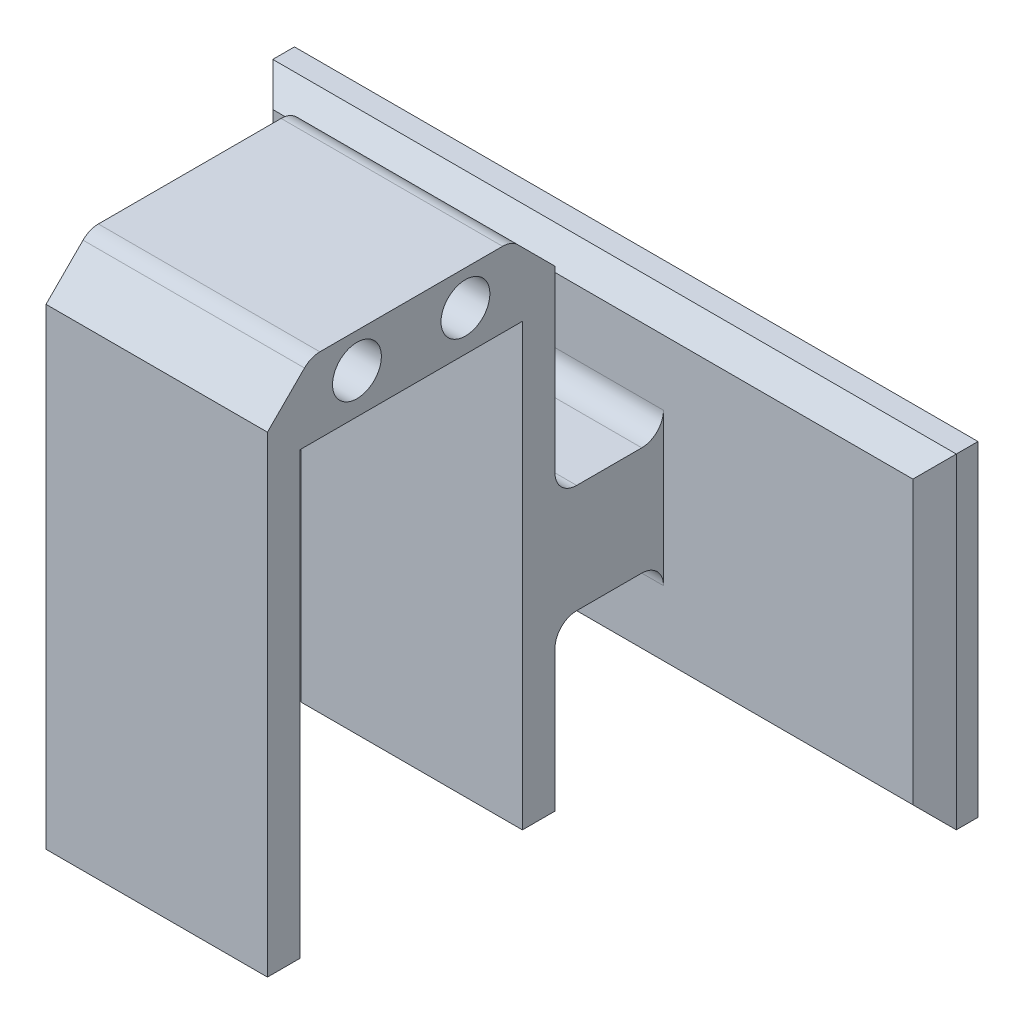
SolidWorks part; units mm, degrees
ref_plane "Front Plane" through (0, 0, 0) normal (0, 0, 1) x (1, 0, 0)
ref_plane "Top Plane" through (0, 0, 0) normal (0, 1, 0) x (1, 0, 0)
ref_plane "Right Plane" through (0, 0, 0) normal (1, 0, 0) x (0, 0, -1)
sketch "Sketch1" plane through (0, 0, 0) normal (1, 0, 0) x (0, 0, -1)
  line L0 (-10.25, 20.3) -> (10.25, 20.3)
  line L1 (-10.25, -20.3) -> (10.25, -20.3)
  line L2 (-10.25, -20.3) -> (-10.25, 20.3)
  line L4 (10.25, -20.3) -> (10.25, 20.3)
  line L5 (-10.25, -20.3) -> (-13.25, -20.3)
  line L6 (-13.25, -20.3) -> (-13.25, 29.7)
  line L7 (-13.25, 29.7) -> (13.25, 29.7)
  line L8 (10.25, -20.3) -> (13.25, -20.3)
  line L11 (-10.05, 20.1) -> (10.05, 20.1)
  line L13 (13.25, -20.3) -> (13.25, 29.7)
  point P5 (0, 20.3)
  point P6 (-10.25, 0)
  line B0 (-8.8772, 20.1) -> (-10.8742, 20.1) construction
  line B1 (7.4, 20.1) -> (11.2713, 20.1) construction
  line B2 (10.05, 18.0597) -> (10.05, 22.3295) construction
  line B3 (-3.2, -20.1) -> (-12.1258, -20.1) construction
  line B4 (-10.05, -15.1145) -> (-10.05, -21.3251) construction
  line B5 (-10.05, -20.1) -> (10.05, -20.1)
  line B6 (-10.05, -20.1) -> (-10.05, 20.1)
  line B7 (10.05, -20.1) -> (10.05, 20.1)
  circle B8 centre (-5, 24) radius 2.25
  circle B9 centre (5, 24) radius 2.25
  dimension "D1" = 0.2
  dimension "D2" = 0.2
  dimension "D3" = 0.2
  dimension "D4" = 0.2
  dimension "D5" = 3
  dimension "D6" = 50
  dimension "D7" = 3
sketch_block_instance "Block1-1"
sketch_block "Block1"
extrude "Boss-Extrude1" add sketch "Sketch1" along normal blind 20 contours L8 L13 L7 L6 L5 L2 L0 L4 B9 B8
sketch "Sketch2" plane through (0, 0, 0) normal (-1, 0, 0) x (0, 0, 1)
  circle A0 centre (-5, 24) radius 2.25
  circle A1 centre (5, 24) radius 2.25
extrude "Boss-Extrude2" add sketch "Sketch2" against normal blind 10
sketch "Sketch4" plane through (20, 0, 0) normal (1, 0, 0) x (0, 0, -1)
  line L0 (13.25, -20.3) -> (13.25, 29.7) construction
  line L1 (-13.25, 29.7) -> (13.25, 29.7)
  line L2 (-13.25, 29.7) -> (-13.25, 27.2)
  line L3 (-13.25, 27.2) -> (13.25, 27.2)
  line L4 (13.25, 29.7) -> (13.25, 27.2)
  dimension "D1" = 2.5
extrude "Cut-Extrude1" cut sketch "Sketch4" against normal through all
chamfer "Chamfer2" distance 4 angle 45 1 edges at (10, 27.2, -13.25)
chamfer "Chamfer3" distance 4 angle 45 1 edges at (10, 27.2, 13.25)
fillet "Fillet4" radius 2 2 edges at (10, 27.2, -9.25) (10, 27.2, 9.25)
sketch "Sketch7" plane through (20, 0, 0) normal (1, 0, 0) x (0, 0, -1)
  line L0 (13.25, -20.3) -> (13.25, 23.2) construction
  line L3 (23.25, -5.3) -> (13.25, -5.3)
  line L5 (10.25, -20.3) -> (13.25, -20.3) construction
  line L6 (13.25, 4.7) -> (23.25, 4.7)
  line L8 (23.25, 4.7) -> (23.25, -5.3)
  line L9 (13.25, 4.7) -> (13.25, -5.3)
  dimension "D1" = 10
  dimension "D2" = 15
extrude "Boss-Extrude5" add sketch "Sketch7" against normal up to surface (20 mm away) up to face at (0, 9.4758, 0)
fillet "Fillet6" radius 2 2 edges at (10, 4.7, -13.25) (10, -5.3, -13.25)
sketch "Sketch8" plane through (0, 0, -23.25) normal (0, 0, -1) x (-1, 0, 0)
  line L1 (-45.4, 14.7) -> (17.6, 14.7)
  line L2 (-45.4, 14.7) -> (-45.4, -15.3)
  line L3 (-45.4, -15.3) -> (17.6, -15.3)
  line L4 (17.6, 14.7) -> (17.6, -15.3)
  line L5 (0, 4.7) -> (-20, 4.7) construction
  line L7 (-13.9, 4.7) -> (-13.9, -5.3) construction
  line L8 (-20, -5.3) -> (-20, 4.7) construction
  line L9 (-20, -0.3) -> (0, -0.3) construction
  line L10 (0, 4.7) -> (0, -5.3) construction
  line L11 (0, -5.3) -> (-20, -5.3) construction
  point P10 (-13.9, 14.7)
  point P17 (-45.4, -0.3)
  dimension "D1" = 63
  dimension "D2" = 30
  dimension "D3" = 6.1
extrude "Boss-Extrude6" add sketch "Sketch8" along normal blind 4
chamfer "Chamfer4" distance 2 angle 45 4 edges at (-17.6, -0.3, -23.25) (13.9, -15.3, -23.25) (45.4, -0.3, -23.25) (13.9, 14.7, -23.25)
fillet "Fillet7" radius 2 2 edges at (10, 4.7, -23.25) (10, -5.3, -23.25)
sketch "Sketch13" plane through (20, 0, 0) normal (1, 0, 0) x (0, 0, -1)
  line L14 (13.25, 23.2) -> (9.8358, 26.6142)
  line L15 (8.4216, 27.2) -> (-8.4216, 27.2)
  line L16 (-9.8358, 26.6142) -> (-13.25, 23.2)
  line L17 (-13.25, 23.2) -> (-13.25, -20.3)
  line L18 (-13.25, -20.3) -> (-10.25, -20.3)
  line L19 (-10.25, -20.3) -> (-10.25, 20.3)
  line L20 (-10.25, 20.3) -> (10.25, 20.3)
  line L21 (10.25, 20.3) -> (10.25, -20.3)
  line L22 (10.25, -20.3) -> (13.25, -20.3)
  line L23 (13.25, -20.3) -> (13.25, -7.3)
  line L24 (15.25, -5.3) -> (21.25, -5.3)
  line L25 (23.25, -7.3) -> (23.25, 6.7)
  line L26 (21.25, 4.7) -> (15.25, 4.7)
  line L27 (13.25, 6.7) -> (13.25, 23.2)
  line L28 (13.25, 23.2) -> (9.8358, 26.6142)
  line L29 (8.4216, 27.2) -> (-8.4216, 27.2)
  line L30 (-9.8358, 26.6142) -> (-13.25, 23.2)
  line L31 (-13.25, 23.2) -> (-13.25, -20.3)
  line L32 (-13.25, -20.3) -> (-10.25, -20.3)
  line L33 (-10.25, -20.3) -> (-10.25, 20.3)
  line L34 (-10.25, 20.3) -> (10.25, 20.3)
  line L35 (10.25, 20.3) -> (10.25, -20.3)
  line L36 (10.25, -20.3) -> (13.25, -20.3)
  line L37 (13.25, -20.3) -> (13.25, -7.3)
  line L38 (15.25, -5.3) -> (21.25, -5.3)
  line L39 (23.25, -7.3) -> (23.25, 6.7)
  line L40 (21.25, 4.7) -> (15.25, 4.7)
  line L41 (13.25, 6.7) -> (13.25, 23.2)
  circle A0 centre (5, 24) radius 2.25 construction
  circle A1 centre (-5, 24) radius 2.25 construction
  circle A2 centre (5, 24) radius 2.25
  circle A3 centre (-5, 24) radius 2.25
  arc A6 (9.8358, 26.6142) -> (8.4216, 27.2) centre (8.4216, 25.2) ccw
  arc A7 (-8.4216, 27.2) -> (-9.8358, 26.6142) centre (-8.4216, 25.2) ccw
  arc A8 (15.25, -5.3) -> (13.25, -7.3) centre (15.25, -7.3) ccw
  arc A9 (23.25, -7.3) -> (21.25, -5.3) centre (21.25, -7.3) ccw
  arc A10 (21.25, 4.7) -> (23.25, 6.7) centre (21.25, 6.7) ccw
  arc A11 (13.25, 6.7) -> (15.25, 4.7) centre (15.25, 6.7) ccw
  arc A12 (9.8358, 26.6142) -> (8.4216, 27.2) centre (8.4216, 25.2) ccw
  arc A13 (-8.4216, 27.2) -> (-9.8358, 26.6142) centre (-8.4216, 25.2) ccw
  arc A14 (15.25, -5.3) -> (13.25, -7.3) centre (15.25, -7.3) ccw
  arc A15 (23.25, -7.3) -> (21.25, -5.3) centre (21.25, -7.3) ccw
  arc A16 (21.25, 4.7) -> (23.25, 6.7) centre (21.25, 6.7) ccw
  arc A17 (13.25, 6.7) -> (15.25, 4.7) centre (15.25, 6.7) ccw
  dimension "D1" = 0
extrude "Boss-Extrude7" add sketch "Sketch13" along normal blind 0.41
